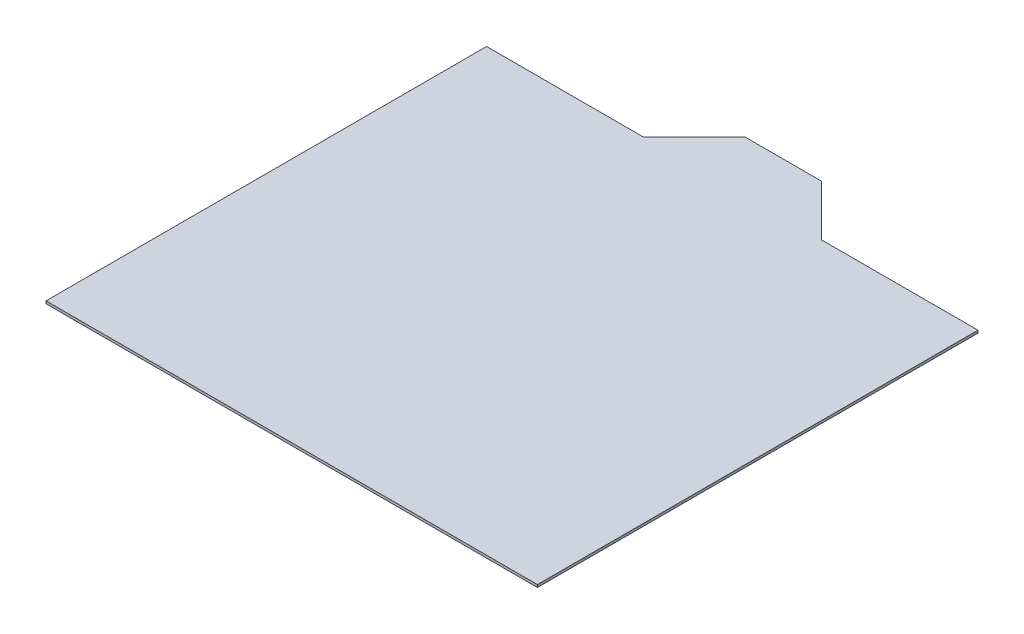
SolidWorks part; units mm, degrees
ref_plane "Front Plane" through (0, 0, 0) normal (0, 0, 1) x (1, 0, 0)
ref_plane "Top Plane" through (0, 0, 0) normal (0, 1, 0) x (1, 0, 0)
ref_plane "Right Plane" through (0, 0, 0) normal (1, 0, 0) x (0, 0, -1)
sketch "Sketch1" plane through (0, 0, 0) normal (0, 1, 0) x (1, 0, 0)
  line L0 (0, 130) -> (0, 160)
  line L1 (-145, -130) -> (145, -130)
  line L2 (-145, -130) -> (-145, 130)
  line L3 (-145, 130) -> (145, 130)
  line L4 (145, -130) -> (145, 130)
  line L5 (-145, -130) -> (145, 130) construction
  line L6 (-145, 130) -> (145, -130) construction
  line L7 (0, -55) -> (0, 55) construction
  line L8 (-22.5, 160) -> (22.5, 160)
  line L9 (22.5, 160) -> (52.5, 130)
  line L10 (-22.5, 160) -> (-52.5, 130)
  point P0 (0, 0)
  point P13 (0, 160)
  dimension "D1" = 260
  dimension "D2" = 290
  dimension "D3" = 30
  dimension "D4" = 45
extrude "Boss-Extrude1" add sketch "Sketch1" along normal blind 1.5 contours L1 L4 L3 L2 | L8 L10 L3 L0 | L9 L8 L0 L3
